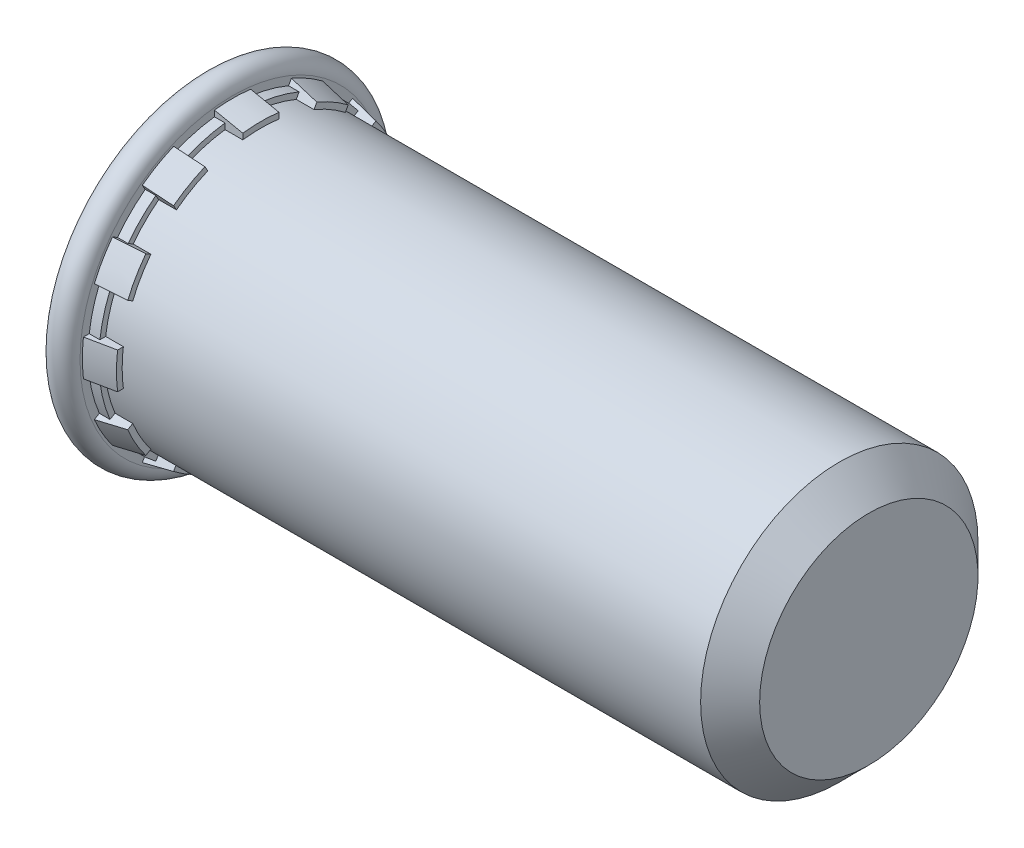
SolidWorks part; units mm, degrees
revolve "BaseBody" add sketch "BodySke" angle 360 about L6
sketch "BodySke" plane through (0, 0, 0) normal (0, 0, 1) x (1, 0, 0)
  line L0 (0, 0) -> (0, 4.3663)
  line L1 (0.8128, 4.3713) -> (0.8128, 4.3053)
  line L2 (0.8128, 4.3053) -> (1.6256, 4.1402)
  line L3 (1.6256, 3.9751) -> (18.2042, 3.9751)
  line L4 (19.05, 3.1293) -> (19.05, 0)
  line L5 (19.05, 0) -> (0, 0)
  line L6 (0, 0) -> (50.554, 0) construction
  line L7 (1.6256, 4.1402) -> (1.6256, 3.9751)
  line L8 (19.05, 3.1293) -> (18.2042, 3.9751)
  line L9 (-9.525, 4.7752) -> (9.525, 4.7752) construction
  line L11 (3.0353, 19.05) -> (3.0353, -3.175) construction
  line L13 (9.525, -4.7752) -> (-9.525, -4.7752) construction
  line L14 (0.0051, 4.3713) -> (0.0051, 4.3663)
  line L15 (0, 4.3663) -> (0.0051, 4.3663)
  arc A0 (0.0051, 4.3713) -> (0.8128, 4.3713) centre (0.4089, 4.3713) cw
  dimension "Body_ch_ang" = 45
  dimension "Length" = 19.05
  dimension "H_dia" = 9.5504
  dimension "Shoulder_lower_dia" = 8.6106
  dimension "Shoulder_upper_dia" = 8.2804
  dimension "D1" = 0.0051
  dimension "D2" = 0.0051
  dimension "Shoulder_ht" = 1.6256
  dimension "Advance" = 1.4097
  dimension "Minor_dia" = 6.2586
  dimension "Diameter" = 7.9502
  dimension "T_dim" = 0.8128
cosmetic thread "ThreadCosmetic" [suppressed] parameters "Thread_length"=14.986, "Thread_minor"=6.2586
extrude "RibCut1" cut sketch "RibCut1Ske" against normal blind 0.508
sketch "RibCut1Ske" plane through (1.6256, 0, 0) normal (1, 0, 0) x (0, 0, -1)
  line L0 (0.5189, 3.9411) -> (0.5189, 4.7469)
  line L1 (1.5212, 3.6725) -> (1.9241, 4.3704)
  line L2 (0, 0) -> (0, 4.9784) construction
  line L3 (0, 0) -> (0.5189, 3.9411) construction
  line L4 (0, 0) -> (1.5212, 3.6725) construction
  arc A1 (1.5212, 3.6725) -> (0.5189, 3.9411) centre (0, 0) ccw
  arc A2 (1.9241, 4.3704) -> (0.5189, 4.7469) centre (0, 0) ccw
  dimension "Angle" = 30
  dimension "Inner_dia" = 7.9502
  dimension "Outer_dia" = 9.5504
  dimension "Rib_root_half_angle" = 7.5
  dimension "Rib_root_gap_angle" = 15
ref_plane "Plane1" through (0, 0, 0) normal (0, 0, 1) x (1, 0, 0)
ref_plane "Plane2" through (0, 0, 0) normal (0, 1, 0) x (1, 0, 0)
ref_plane "Plane3" through (0, 0, 0) normal (1, 0, 0) x (0, 0, -1)
sketch "ThdSchSke" plane through (0, 0, 0) normal (0, 0, 1) x (1, 0, 0)
  line L0 (4.064, -3.1293) -> (3.4718, -3.9751)
  line L1 (4.064, -3.1293) -> (4.6562, -3.9751)
  line L2 (4.6562, -3.9751) -> (4.6562, -4.9689)
  line L3 (-3.175, 0) -> (5.1513, 0) construction
  line L5 (4.6562, -4.9689) -> (3.4718, -4.9689)
  line L6 (3.4718, -4.9689) -> (3.4718, -3.9751)
  line L7 (0, 4.3663) -> (0, -4.3663) construction
  dimension "Diameter" = 7.9502
  dimension "SideAngle" = 55
  dimension "VeeAngle" = 70
  dimension "Thread_minor" = 6.2586
  dimension "Overcut" = 9.9377
  dimension "Start" = 4.064
revolve "ThreadSchematic" [suppressed] cut sketch "ThdSchSke" angle 360 about L3
pattern_linear "ThdSchPat" [suppressed]
sketch "RibCut2Ske" plane through (1.6256, 0, 0) normal (1, 0, 0) x (0, 0, -1)
  line L0 (0.5189, 4.1076) -> (0.5189, 4.7469)
  line L1 (1.6044, 3.8167) -> (1.9241, 4.3704)
  line L2 (0.5189, 3.9411) -> (0.5189, 5.7528) construction
  line L3 (0, 0) -> (0, 5.0239) construction
  line L4 (0, 0) -> (0.5189, 3.9411) construction
  line L5 (0, 0) -> (1.5212, 3.6725) construction
  line L6 (1.5212, 3.6725) -> (2.4306, 5.2477) construction
  arc A1 (1.6044, 3.8167) -> (0.5189, 4.1076) centre (0, 0) ccw
  arc A2 (1.9241, 4.3704) -> (0.5189, 4.7469) centre (0, 0) ccw
  circle A4 centre (0, 0) radius 3.9751 construction
  dimension "Angle" = 30
  dimension "Outer_dia" = 9.5504
  dimension "Rib_root_half_angle" = 7.5
  dimension "Rib_root_gap_angle" = 15
extrude "RibCut2" cut sketch "RibCut2Ske" against normal blind 0.8128
pattern_circular "RibCutsPat" count 12 every 30 about axis through (0, 0, 0) along (1, 0, 0) of "RibCut2", "RibCut1"
equation "' \"Length@BodySke\" = 0.75"
equation "' \"H_dia@BodySke\" = 0.337"
equation "' \"Start@ThdSchSke\" = 0.135"
equation "' \"Diameter@BodySke\" = 0.25"
equation "' \"Minor_dia@BodySke\" =0.1905"
equation "' \"Minor_dia@BodySke\" = 0.1905"
equation "' \"Advance@BodySke\" = 0.05"
equation "\"T_dim@BodySke\" = \"Start@ThdSchSke\" * 0.2"
equation "\"Shoulder_ht@BodySke\" = \"Start@ThdSchSke\" * 0.4"
equation "\"Shoulder_lower_dia@BodySke\" = \"H_dia@BodySke\" - \"Start@ThdSchSke\" * 0.2 - .005"
equation "\"Shoulder_upper_dia@BodySke\" = ( \"Shoulder_lower_dia@BodySke\" + \"Diameter@BodySke\" ) /2"
equation "\"Num_ribs@RibCutsPat\" = 12"
equation "\"Angle@RibCutsPat\" = 360 / \"Num_ribs@RibCutsPat\""
equation "\"Angle@RibCut1Ske\" =\"Angle@RibCutsPat\""
equation "\"Rib_root_half_angle@RibCut1Ske\" = \"Angle@RibCut1Ske\" / 4"
equation "\"Rib_root_gap_angle@RibCut1Ske\" = \"Angle@RibCut1Ske\" - (2 * \"Rib_root_half_angle@RibCut1Ske\" )"
equation "\"Inner_dia@RibCut1Ske\" = \"Diameter@BodySke\""
equation "\"Outer_dia@RibCut1Ske\" = \"H_dia@BodySke\""
equation "\"Depth@RibCut1\" =  \"Start@ThdSchSke\" * 0.125"
equation "\"Angle@RibCut2Ske\" =\"Angle@RibCutsPat\""
equation "\"Rib_root_half_angle@RibCut2Ske\" = \"Angle@RibCut1Ske\" / 4"
equation "\"Rib_root_gap_angle@RibCut2Ske\" = \"Angle@RibCut1Ske\" - (2 * \"Rib_root_half_angle@RibCut1Ske\" )"
equation "\"Rib_root_dia@RibCut2Ske\" = \"Diameter@BodySke\""
equation "\"Inner_dia@RibCut2Ske\" = \"Shoulder_upper_dia@BodySke\""
equation "\"Outer_dia@RibCut2Ske\" = \"H_dia@BodySke\""
equation "\"Depth@RibCut2\" =  \"Start@ThdSchSke\" * 0.2"
equation "\"Thread_length@ThreadCosmetic\" = \"Length@BodySke\" - \"Start@ThdSchSke\""
equation "\"Thread_minor@ThreadCosmetic\" = \"Minor_dia@BodySke\""
equation "\"Thread_minor@ThdSchSke\" = \"Minor_dia@BodySke\""
equation "\"Diameter@ThdSchSke\" = \"Diameter@BodySke\""
equation "\"Overcut@ThdSchSke\" = \"Diameter@BodySke\" * 1.25"
equation "\"Num_threads@ThdSchPat\" = int( \"Thread_length@ThreadCosmetic\" / \"Advance@BodySke\" + 0.999 )  + 1"
equation "\"Advance@ThdSchPat\" = \"Thread_length@ThreadCosmetic\" /  (\"Num_threads@ThdSchPat\" - 1) 'relax it"
equation "\"Num_threads@ThdSchPat\" = \"Num_threads@ThdSchPat\" - sgn( \"Num_threads@ThdSchPat\" - 1) '---chamfered tips only---"
